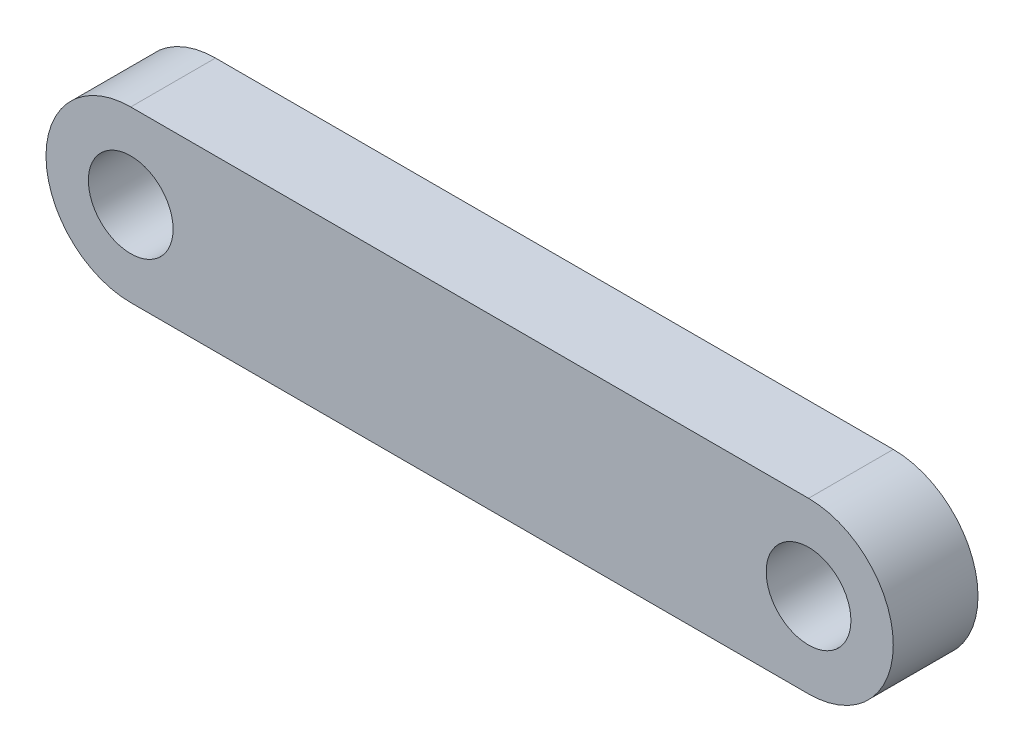
SolidWorks part; units mm, degrees
ref_plane "前基準面" through (0, 0, 0) normal (0, 0, 1) x (1, 0, 0)
ref_plane "上基準面" through (0, 0, 0) normal (0, 1, 0) x (1, 0, 0)
ref_plane "右基準面" through (0, 0, 0) normal (1, 0, 0) x (0, 0, -1)
sketch "草圖1" plane through (0, 0, 0) normal (0, 0, 1) x (1, 0, 0)
  line L0 (-8, 2.0004) -> (8, 2.0004)
  line L1 (-8, -1.9996) -> (8, -1.9996)
  arc A0 (-8, 2.0004) -> (-8, -1.9996) centre (-8, 0.0004) ccw
  arc A1 (8, -1.9996) -> (8, 2.0004) centre (8, 0.0004) ccw
  circle A2 centre (-8, 0.0004) radius 1
  circle A3 centre (8, 0.0004) radius 1
  dimension "D1" = 16
  dimension "D2" = 2
  dimension "D3" = 2
  dimension "D4" = 2
  dimension "D5" = 8
extrude "填料-伸長1" add sketch "草圖1" along normal blind 2
